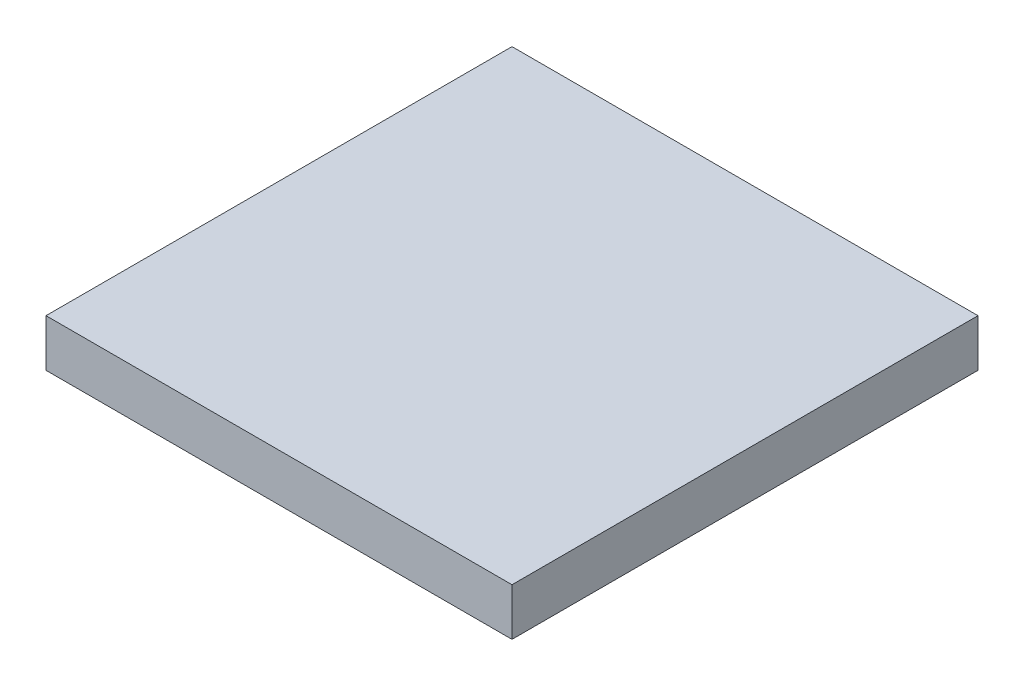
SolidWorks part; units mm, degrees
ref_plane "Front Plane" through (0, 0, 0) normal (0, 0, 1) x (1, 0, 0)
ref_plane "Top Plane" through (0, 0, 0) normal (0, 1, 0) x (1, 0, 0)
ref_plane "Right Plane" through (0, 0, 0) normal (1, 0, 0) x (0, 0, -1)
sketch "Sketch2" plane through (0, 0, 0) normal (0, 1, 0) x (1, 0, 0)
  line L0 (-125, -125) -> (125, 125) construction
  line L1 (-125, 125) -> (125, 125)
  line L2 (-125, 125) -> (-125, -125)
  line L3 (-125, -125) -> (125, -125)
  line L4 (125, 125) -> (125, -125)
  line L5 (-125, 125) -> (125, -125) construction
  point P4 (0, 0)
  dimension "D1" = 250
extrude "Boss-Extrude1" add sketch "Sketch2" along normal blind 25.4
sketch "Sketch3" plane through (0, 25.4, 0) normal (0, 1, 0) x (1, 0, 0)
  circle A0 centre (0, 0) radius 25
  dimension "D1" = 50
